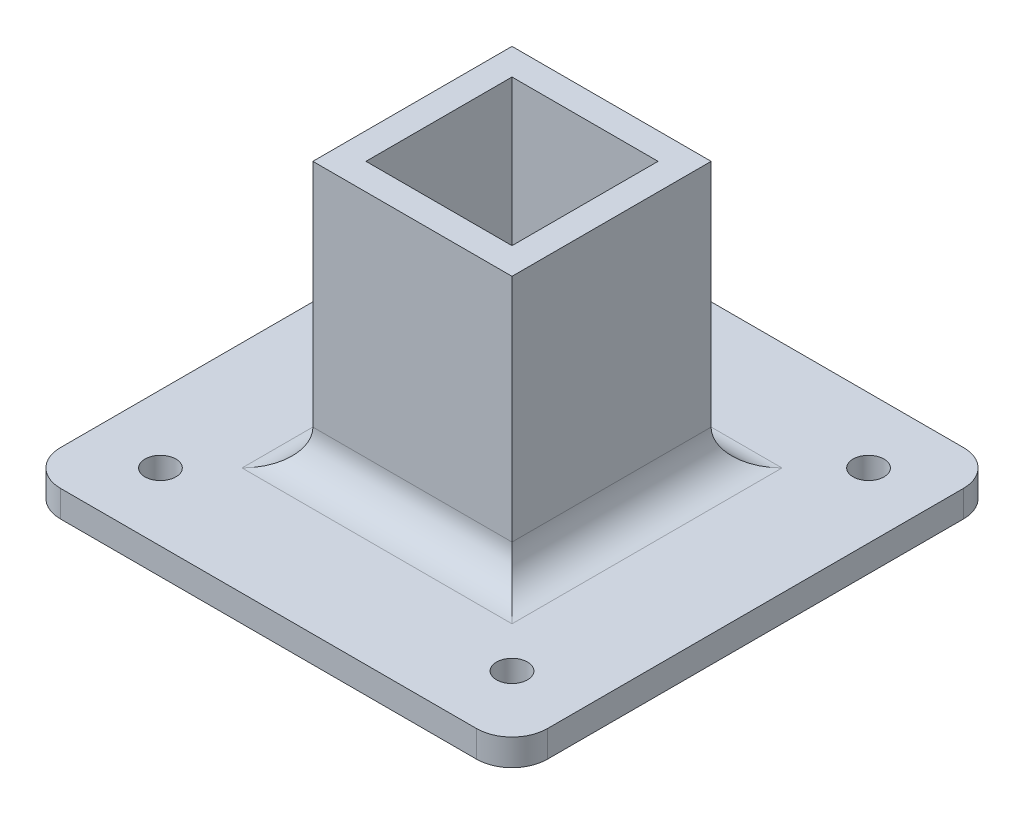
SolidWorks part; units mm, degrees
ref_plane "Front Plane" through (0, 0, 0) normal (0, 0, 1) x (1, 0, 0)
ref_plane "Top Plane" through (0, 0, 0) normal (0, 1, 0) x (1, 0, 0)
ref_plane "Right Plane" through (0, 0, 0) normal (1, 0, 0) x (0, 0, -1)
sketch "Sketch1" plane through (0, 0, 0) normal (0, 1, 0) x (1, 0, 0)
  line L0 (0, 0) -> (0, -12.8421) construction
  line L1 (-27.5, 27.5) -> (27.5, 27.5)
  line L2 (-27.5, 27.5) -> (-27.5, -27.5)
  line L3 (-27.5, -27.5) -> (27.5, -27.5)
  line L4 (27.5, 27.5) -> (27.5, -27.5)
  line L5 (-27.5, 27.5) -> (27.5, -27.5) construction
  line L6 (-27.5, -27.5) -> (27.5, 27.5) construction
  circle A0 centre (20.1404, 20.1404) radius 1.75
  circle A1 centre (-19.8596, -19.8596) radius 1.75
  circle A2 centre (-20.1404, 20.1404) radius 1.75
  circle A3 centre (19.8596, -19.8596) radius 1.75
  point P0 (0, 0)
  dimension "D4" = 3.5
  dimension "D5" = 40
  dimension "D1" = 55
  dimension "D2" = 55
  dimension "D3" = 40
extrude "Boss-Extrude1" add sketch "Sketch1" along normal blind 3
sketch "Sketch2" plane through (0, 3, 0) normal (0, 1, 0) x (1, 0, 0)
  line L0 (27.5, 27.5) -> (-27.5, -27.5) construction
  line L1 (8.25, -8.25) -> (-8.25, -8.25)
  line L2 (11.25, -11.25) -> (-11.25, -11.25)
  line L3 (11.25, -11.25) -> (11.25, 11.25)
  line L4 (11.25, 11.25) -> (-11.25, 11.25)
  line L5 (-11.25, -11.25) -> (-11.25, 11.25)
  line L6 (11.25, -11.25) -> (-11.25, 11.25) construction
  line L7 (11.25, 11.25) -> (-11.25, -11.25) construction
  line L8 (-8.25, -8.25) -> (-8.25, 8.25)
  line L9 (8.25, 8.25) -> (-8.25, 8.25)
  line L10 (8.25, -8.25) -> (8.25, 8.25)
  point P4 (0, 0)
  dimension "D1" = 22.5
  dimension "D2" = 3
extrude "Boss-Extrude2" add sketch "Sketch2" along normal blind 30
sketch "Sketch3" plane through (0, 3, 0) normal (0, 1, 0) x (1, 0, 0)
  line L4 (8.25, -8.25) -> (8.25, 8.25)
  line L5 (8.25, 8.25) -> (-8.25, 8.25)
  line L6 (-8.25, 8.25) -> (-8.25, -8.25)
  line L7 (-8.25, -8.25) -> (8.25, -8.25)
  line L8 (8.25, -8.25) -> (8.25, 8.25)
  line L9 (8.25, 8.25) -> (-8.25, 8.25)
  line L10 (-8.25, 8.25) -> (-8.25, -8.25)
  line L11 (-8.25, -8.25) -> (8.25, -8.25)
  dimension "D1" = 0
extrude "Cut-Extrude1" cut sketch "Sketch3" against normal blind 30
fillet "Fillet1" radius 4 4 edges at (0, 3, -11.25) (-11.25, 3, 0) (0, 3, 11.25) (11.25, 3, 0)
fillet "Fillet2" radius 4 4 edges at (-27.5, 1.5, 27.5) (27.5, 1.5, 27.5) (-27.5, 1.5, -27.5) (27.5, 1.5, -27.5)
